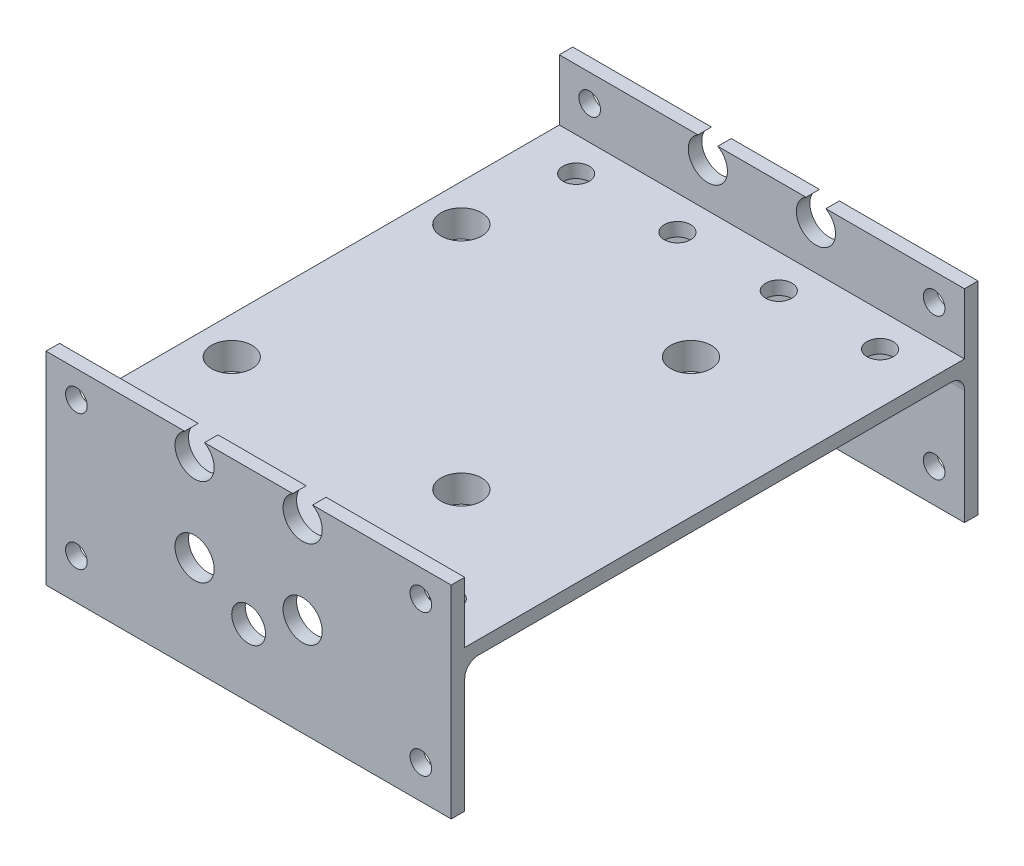
SolidWorks part; units mm, degrees
material "PET"
ref_plane "前视基准面" through (0, 0, 0) normal (0, 0, 1) x (1, 0, 0)
ref_plane "上视基准面" through (0, 0, 0) normal (0, 1, 0) x (1, 0, 0)
ref_plane "右视基准面" through (0, 0, 0) normal (1, 0, 0) x (0, 0, -1)
other "Configuration Table"
sketch "草图1" plane through (0, 0, 0) normal (0, 1, 0) x (1, 0, 0)
  line L1 (-30, -39) -> (30, -39)
  line L2 (-30, -39) -> (-30, 39)
  line L3 (-30, 39) -> (30, 39)
  line L4 (30, -39) -> (30, 39)
  line L5 (-30, -39) -> (30, 39) construction
  line L6 (-30, 39) -> (30, -39) construction
  point P0 (0, 0)
  dimension "D1" = 60
  dimension "D2" = 78
extrude "凸台-拉伸1" add sketch "草图1" along normal blind 2
sketch "草图2" plane through (0, 2, 0) normal (0, 1, 0) x (1, 0, 0)
  line L0 (-30, 0) -> (30, 0) construction
  line L1 (-30, 39) -> (-30, -39) construction
  line L2 (30, -39) -> (30, 39) construction
  line L3 (-24.5, 0) -> (-24.5, 17) construction
  circle A0 centre (-24.5, 17) radius 2.1
  circle A1 centre (9.5, 17) radius 2.1
  circle A2 centre (9.5, -17) radius 2.1
  circle A3 centre (-24.5, -17) radius 2.1
  dimension "D3" = 4.2
  dimension "D4" = 34
  dimension "D5" = 17
  dimension "D6" = 4.2
  dimension "D1" = 17
  dimension "D2" = 5.5
extrude "切除-拉伸1" cut sketch "草图2" against normal blind 12
sketch "草图3" plane through (0, 0, 39) normal (0, 0, 1) x (1, 0, 0)
  line L0 (-30, 2) -> (30, 0) construction
  line L1 (30, 2) -> (-30, 0) construction
  line L4 (-30, -9) -> (-30, 11)
  line L6 (30, -9) -> (30, 11)
  line L7 (-30, -9) -> (30, 11) construction
  line L8 (-30, 11) -> (30, -9) construction
  line L11 (-30, -9) -> (-30, -19)
  line L12 (-30, -19) -> (30, -19)
  line L13 (30, -19) -> (30, -9)
  line L14 (-30, 11) -> (30, 11)
  point P8 (0, 1)
  dimension "D1" = 20
  dimension "D2" = 10
extrude "凸台-拉伸2" add sketch "草图3" against normal blind 2
ref_plane "基准面1" through (0, 0, 0) normal (0, 0, 1) x (1, 0, 0)
mirror "镜向1" about plane through (0, 0, 0) normal (0, 0, 1) of "凸台-拉伸2"
sketch "草图4" plane through (0, 0, 39) normal (0, 0, 1) x (1, 0, 0)
  line L0 (-30, -4) -> (30, -4) construction
  line L1 (-30, 11) -> (-30, -19) construction
  line L2 (30, 11) -> (30, -19) construction
  line L3 (-25.5, -4) -> (-25.5, 7) construction
  line L4 (0, 12) -> (0, -8) construction
  circle A0 centre (-25.5, 7) radius 1.6
  circle A3 centre (25.5, 7) radius 1.6
  circle A4 centre (-25.5, -13) radius 1.6
  circle A5 centre (25.5, -14) radius 1.6
  point P11 (0, 0)
  point P21 (0, 0)
  dimension "D1" = 3.2
  dimension "D3" = 25.5
  dimension "D4" = 9
  dimension "D5" = 10
  dimension "D6" = 3.2
  dimension "D7" = 3.2
  dimension "D2" = 11
extrude "切除-拉伸2" cut sketch "草图4" against normal blind 126
sketch "草图5" plane through (0, 2, 0) normal (0, 1, 0) x (1, 0, 0)
  line L0 (0, 37) -> (0, -37) construction
  line L6 (-16.5, 0) -> (16.5, 0) construction
  circle A1 centre (-22.5, 32) radius 1.9469
  circle A2 centre (-7.5, 32) radius 1.9469
  circle A3 centre (7.5, 32) radius 1.9469
  circle A4 centre (22.5, 32) radius 1.9469
  circle A5 centre (22.5, -32) radius 1.9469
  circle A6 centre (7.5, -32) radius 1.9469
  circle A7 centre (-7.5, -32) radius 1.9469
  circle A8 centre (-22.5, -32) radius 1.9469
  point P2 (0, 0)
  point P8 (0, 0)
  dimension "D1" = 32
  dimension "D2" = 22.5
  dimension "D3" = 4
extrude "切除-拉伸3" cut sketch "草图5" against normal blind 10
sketch "草图6" plane through (0, 2, 0) normal (0, 1, 0) x (1, 0, 0)
  circle A0 centre (-24.5, 17) radius 4
  circle A1 centre (9.5, 17) radius 4
  circle A2 centre (-24.5, -17) radius 4
  circle A3 centre (9.5, -17) radius 4
  circle A4 centre (-24.5, 17) radius 2.1
  circle A5 centre (9.5, 17) radius 2.1
  circle A6 centre (-24.5, -17) radius 2.1
  circle A8 centre (9.5, -17) radius 2.1
  dimension "D1" = 8
  dimension "D2" = 8
  dimension "D3" = 8
  dimension "D4" = 8
  dimension "D5" = 4.2
  dimension "D6" = 4.2
  dimension "D7" = 4.2
  dimension "D8" = 4.2
extrude "凸台-拉伸3" add sketch "草图6" against normal blind 5
fillet "圆角1" radius 2 2 edges at (0, 0, 37) (0, 0, -37)
sketch "草图8" plane through (0, 0, -39) normal (0, 0, -1) x (-1, 0, 0)
  circle A0 centre (0, -9) radius 2.5
  point P4 (0, 0)
  dimension "D1" = 5
extrude "切除-拉伸5" cut sketch "草图8" against normal blind 113
sketch "草图9" plane through (0, 2, 0) normal (0, 1, 0) x (1, 0, 0)
  circle A0 centre (-24.5, -17) radius 3
  circle A1 centre (9.5, -17) radius 3
  circle A2 centre (-24.5, 17) radius 3
  circle A3 centre (9.5, 17) radius 3
  dimension "D1" = 6
  dimension "D2" = 6
  dimension "D3" = 6
  dimension "D4" = 6
extrude "切除-拉伸6" cut sketch "草图9" against normal blind 4
sketch "草图10" plane through (0, 0, 0) normal (0, -1, 0) x (-1, 0, 0)
  line L0 (-16.5, 0) -> (16.5, 0) construction
  line L1 (33.2702, 23.1872) -> (-14.7787, 23.1872)
  line L2 (33.2702, 23.1872) -> (33.2702, -23.1872)
  line L3 (33.2702, -23.1872) -> (-14.7787, -23.1872)
  line L4 (-14.7787, 23.1872) -> (-14.7787, -23.1872)
  line L5 (33.2702, 23.1872) -> (-14.7787, -23.1872) construction
  line L6 (33.2702, -23.1872) -> (-14.7787, 23.1872) construction
  point P0 (9.2458, 0)
extrude "切除-拉伸7" [suppressed] cut sketch "草图10" along normal blind 26
sketch "草图11" plane through (0, 0, -39) normal (0, 0, -1) x (-1, 0, 0)
  line L0 (-25.5, 7) -> (-8, 7) construction
  line L1 (-8, 7) -> (-8, -4.5) construction
  circle A0 centre (-8, -4.5) radius 2.9
  circle A1 centre (-25.5, -14) radius 1.6 construction
  dimension "D3" = 5.8
  dimension "D2" = 9.5
  dimension "D1" = 17.5
extrude "切除-拉伸8" cut sketch "草图11" against normal blind 3.3
ref_plane "基准面2" through (0, 0, 0) normal (1, 0, 0) x (0, 0, -1)
mirror "镜向2" about plane through (0, 0, 0) normal (1, 0, 0) of "切除-拉伸8"
mirror "镜向3" about plane through (0, 0, 0) normal (0, 0, 1) of "镜向2", "切除-拉伸8"
sketch "草图12" plane through (0, 0, -39) normal (0, 0, -1) x (-1, 0, 0)
  line L0 (-8, -4.5) -> (-8, 11) construction
  line L1 (-30, 11) -> (30, 11) construction
  circle A0 centre (-8, 8.5) radius 2.9
  circle A1 centre (-25.5, 7) radius 1.6 construction
  point P4 (-8, 7.5)
  dimension "D1" = 1.5
  dimension "D2" = 5.8
extrude "切除-拉伸9" cut sketch "草图12" against normal blind 87
sketch "草图13" plane through (0, 0, -39) normal (0, 0, -1) x (-1, 0, 0)
  line L0 (-8, 8.5) -> (8, 8.5) construction
  circle A0 centre (8, 8.5) radius 2.9
  dimension "D2" = 5.8
  dimension "D1" = 16
extrude "切除-拉伸10" cut sketch "草图13" against normal blind 87
